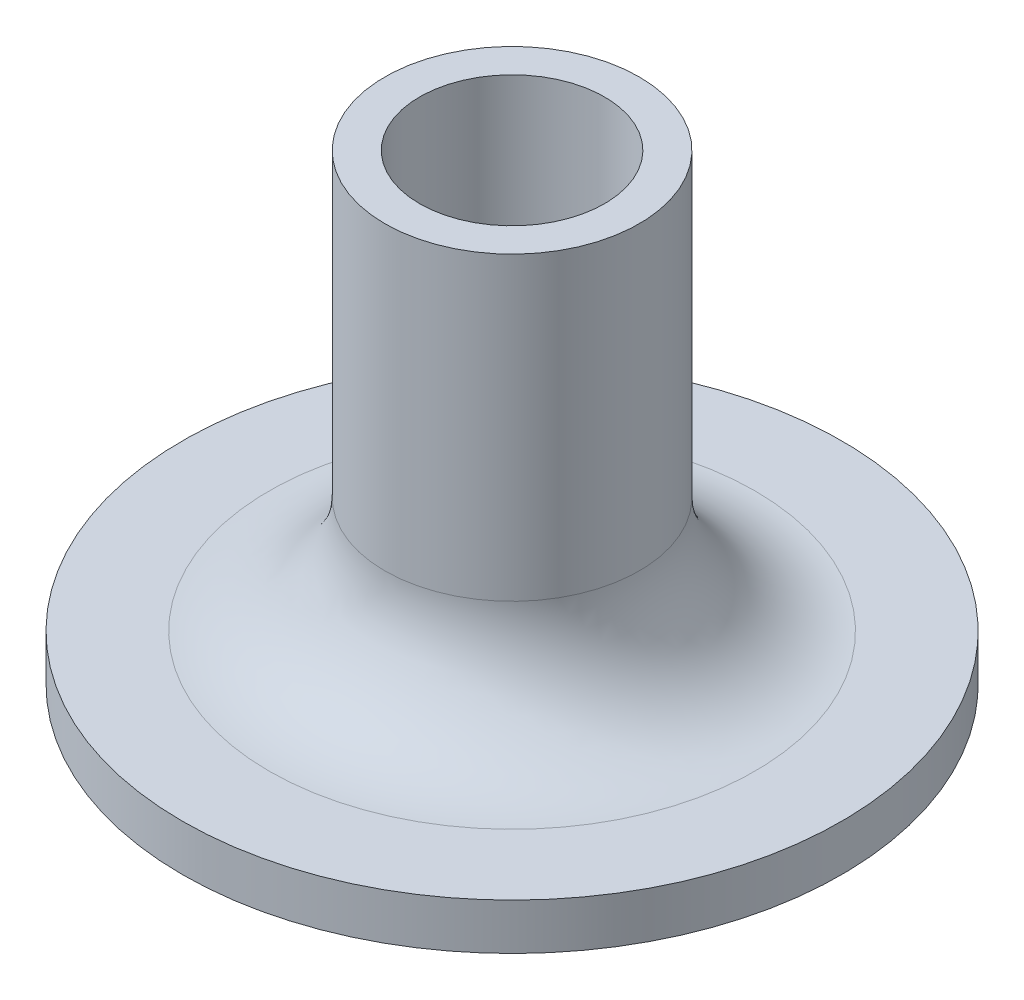
SolidWorks part; units mm, degrees
ref_plane "Front Plane" through (0, 0, 0) normal (0, 0, 1) x (1, 0, 0)
ref_plane "Top Plane" through (0, 0, 0) normal (0, 1, 0) x (1, 0, 0)
ref_plane "Right Plane" through (0, 0, 0) normal (1, 0, 0) x (0, 0, -1)
sketch "Sketch1" plane through (0, 0, 0) normal (0, 1, 0) x (1, 0, 0)
  circle A0 centre (0, 0) radius 14.25
  dimension "D1" = 28.5
extrude "Boss-Extrude1" add sketch "Sketch1" along normal blind 2
sketch "Sketch2" plane through (0, 2, 0) normal (0, 1, 0) x (1, 0, 0)
  circle A0 centre (0, 0) radius 5.5
  circle A1 centre (0, 0) radius 4
  dimension "D1" = 8
  dimension "D2" = 1.5
extrude "Boss-Extrude2" add sketch "Sketch2" along normal blind 18
fillet "Fillet1" radius 5 1 edges at (0, 2, 5.5)
